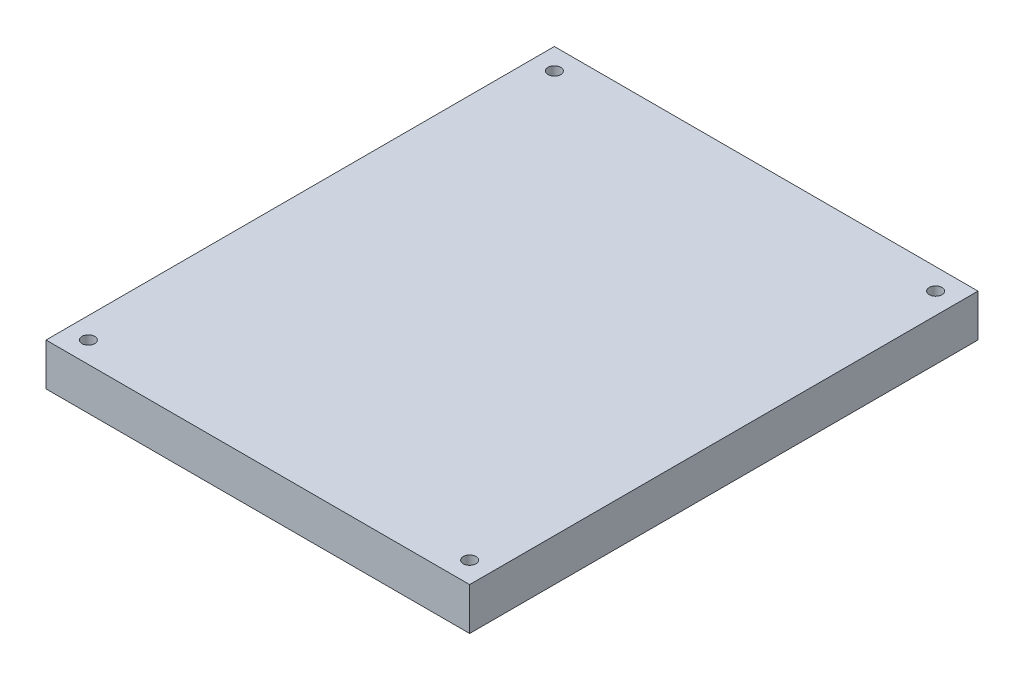
SolidWorks part; units mm, degrees
ref_plane "前视" through (0, 0, 0) normal (0, 0, 1) x (1, 0, 0)
ref_plane "上视" through (0, 0, 0) normal (0, 1, 0) x (1, 0, 0)
ref_plane "右视" through (0, 0, 0) normal (1, 0, 0) x (0, 0, -1)
sketch "Sketch1" plane through (0, 0, 0) normal (0, 1, 0) x (1, 0, 0)
  line L1 (-4.4335, 4.6552) -> (95.5665, 4.6552)
  line L2 (-4.4335, 4.6552) -> (-4.4335, -115.3448)
  line L3 (-4.4335, -115.3448) -> (95.5665, -115.3448)
  line L4 (95.5665, 4.6552) -> (95.5665, -115.3448)
  dimension "D1" = 100
  dimension "D2" = 120
extrude "Boss-Extrude1" add sketch "Sketch1" along normal blind 10
sketch "Sketch2" plane through (0, 10, 0) normal (0, 1, 0) x (1, 0, 0)
  line L0 (95.5665, 4.6552) -> (-4.4335, 4.6552) construction
  line L1 (-4.4335, 4.6552) -> (-4.4335, -115.3448) construction
  line L2 (45.5665, 4.6552) -> (45.5665, -115.3448) construction
  line L3 (-4.4335, -115.3448) -> (95.5665, -115.3448) construction
  line L4 (-4.4335, -55.3448) -> (95.5665, -55.3448) construction
  line L5 (95.5665, -115.3448) -> (95.5665, 4.6552) construction
  circle A0 centre (0.5665, -0.3448) radius 1.5
  circle A1 centre (90.5665, -0.3448) radius 1.5
  circle A2 centre (90.5665, -110.3448) radius 1.5
  circle A3 centre (0.5665, -110.3448) radius 1.5
  dimension "D3" = 3
  dimension "D1" = 5
  dimension "D2" = 5
extrude "Cut-Extrude4" cut sketch "Sketch2" against normal through all
